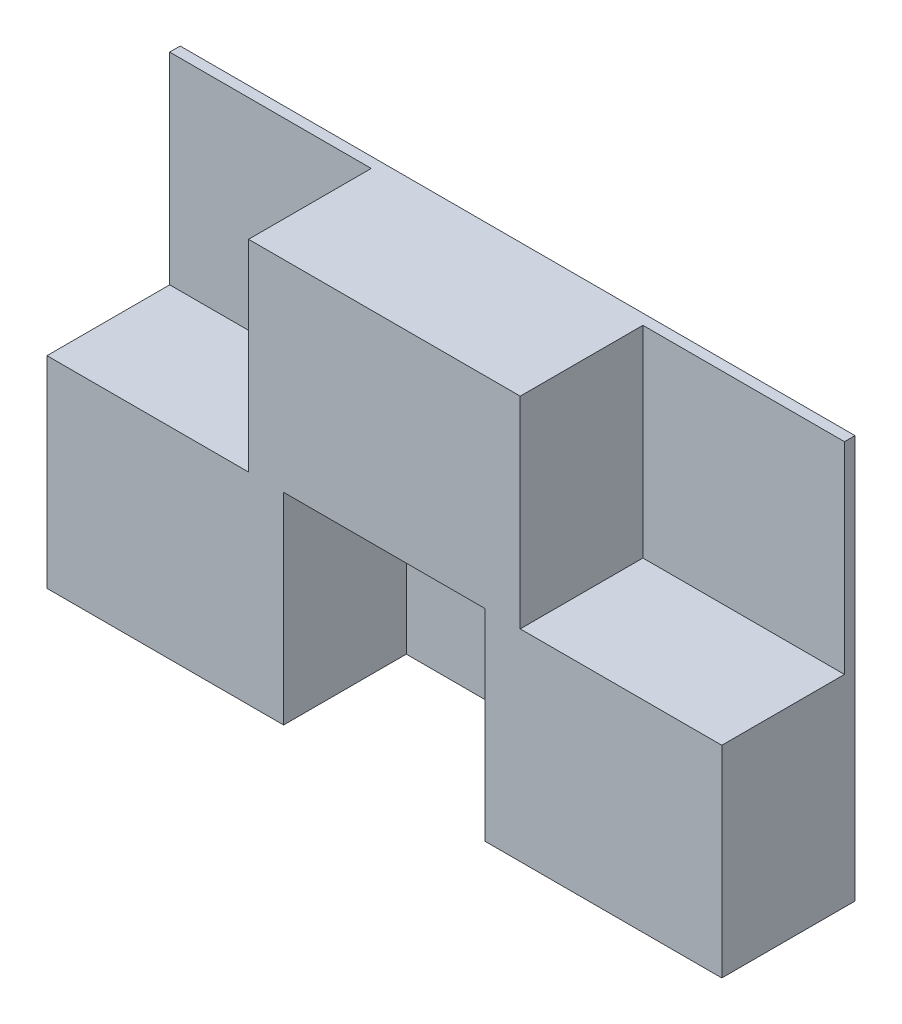
SolidWorks part; units mm, degrees
ref_plane "Front Plane" through (0, 0, 0) normal (0, 0, 1) x (1, 0, 0)
ref_plane "Top Plane" through (0, 0, 0) normal (0, 1, 0) x (1, 0, 0)
ref_plane "Right Plane" through (0, 0, 0) normal (1, 0, 0) x (0, 0, -1)
sketch "Sketch1" plane through (0, 0, 0) normal (0, 0, 1) x (1, 0, 0)
  line L0 (0, 0) -> (36.4561, 0) construction
  line L2 (0, 0) -> (192.5, 0)
  line L3 (0, 0) -> (0, 115)
  line L4 (0, 115) -> (192.5, 115)
  line L5 (192.5, 0) -> (192.5, 115)
  dimension "D1" = 115
  dimension "D2" = 192.5
extrude "Boss-Extrude1" add sketch "Sketch1" along normal blind 3
sketch "Sketch2" plane through (0, 0, 3) normal (0, 0, 1) x (1, 0, 0)
  line L0 (0, 57.5) -> (192.5, 57.5) construction
  line L1 (0, 57.5) -> (0, 0)
  line L2 (0, 115) -> (0, 0) construction
  line L3 (0, 57.5) -> (57.5, 57.5)
  line L4 (57.5, 115) -> (135, 115)
  line L5 (192.5, 57.5) -> (192.5, 0)
  line L6 (57.5, 57.5) -> (57.5, 115)
  line L7 (192.5, 115) -> (0, 115) construction
  line L8 (0, 0) -> (192.5, 0) construction
  line L9 (192.5, 0) -> (125, 0)
  line L10 (0, 0) -> (67.5, 0)
  line L11 (192.5, 57.5) -> (135, 57.5)
  line L12 (135, 115) -> (135, 57.5)
  line L13 (67.5, 57.5) -> (125, 57.5)
  line L14 (67.5, 57.5) -> (67.5, 0)
  line L16 (125, 57.5) -> (125, 0)
  dimension "D1" = 10
  dimension "D2" = 57.5
  dimension "D3" = 57.5
  dimension "D4" = 10
extrude "Boss-Extrude2" add sketch "Sketch2" along normal blind 35
